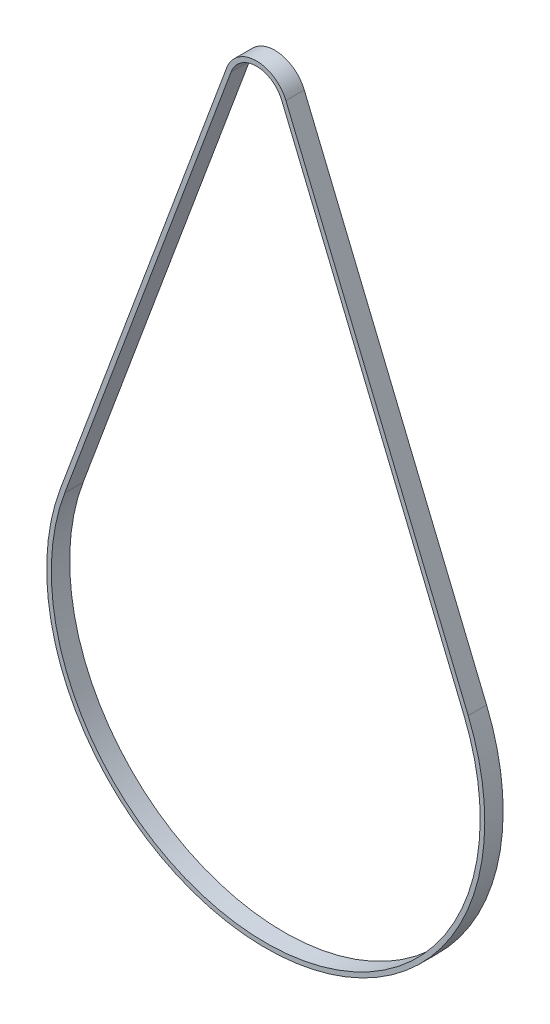
SolidWorks part; units mm, degrees
material "Silicon Rubber"
ref_plane "Front Plane" through (0, 0, 0) normal (0, 0, 1) x (1, 0, 0)
ref_plane "Top Plane" through (0, 0, 0) normal (0, 1, 0) x (1, 0, 0)
ref_plane "Right Plane" through (0, 0, 0) normal (1, 0, 0) x (0, 0, -1)
sketch "Sketch2" plane through (0, 0, 0) normal (0, 0, 1) x (1, 0, 0)
  line L0 (0, 0) -> (1, 0) construction
  line L1 (0, 0) -> (0, 1) construction
  line L6 (-82.077, -137.9108) -> (-27.7736, 8.2414)
  line L7 (-9.8659, 8.5622) -> (49.638, -135.5509)
  arc A1 (49.638, -135.5509) -> (-82.077, -137.9108) centre (-15.7568, -162.5523) cw
  arc A3 (-27.7736, 8.2414) -> (-9.8659, 8.5622) centre (-18.7569, 4.8912) cw
extrude "Extrude-Thin1" add sketch "Sketch2" along normal blind 6 thin thin type mid plane wall 1.5
